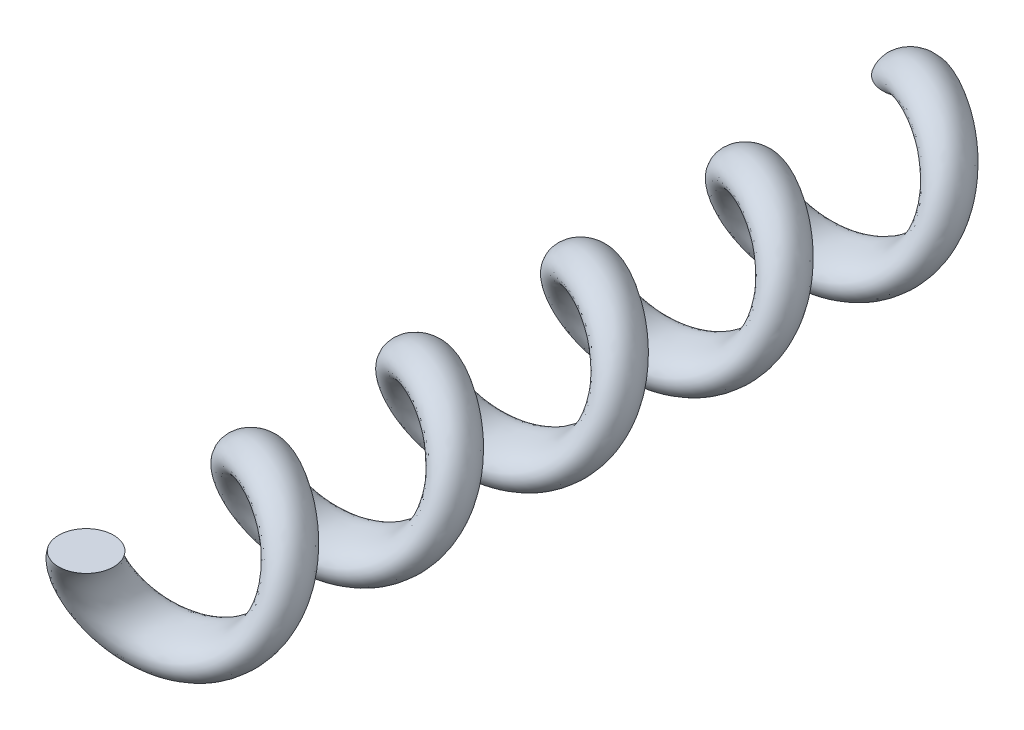
SolidWorks part; units mm, degrees
ref_plane "Front Plane" through (0, 0, 0) normal (0, 0, 1) x (1, 0, 0)
ref_plane "Top Plane" through (0, 0, 0) normal (0, 1, 0) x (1, 0, 0)
ref_plane "Right Plane" through (0, 0, 0) normal (1, 0, 0) x (0, 0, -1)
sketch "Sketch1" plane through (0, 0, 0) normal (0, 0, 1) x (1, 0, 0)
  circle A0 centre (0, 0) radius 2
  dimension "D1" = 4
curve "Helix/Spiral1" pitch 6 height 30 turns 5
ref_plane "Plane1" through (0, 1.4142, 0) normal (0, 1, 0) x (1, 0, 0)
sketch "Sketch2" plane through (0, 1.4142, 0) normal (0, 1, 0) x (1, 0, 0)
  circle A0 centre (-1.4142, 0) radius 1
  spline S0 degree 3 poles (-1.4142, 0) (-1.2301, -0.1243) (-0.7849, -0.3753) (-0.0001, -0.7499) (0.7853, -1.125) (1.451, -1.5) (1.8959, -1.875) (2.0521, -2.25) (1.8959, -2.625) (1.451, -3) (0.5634, -3.5) (-0.5634, -4) (-1.451, -4.5) (-1.8959, -4.875) (-2.0521, -5.25) (-1.8959, -5.625) (-1.451, -6) (-0.5634, -6.5) (0.5634, -7) (1.451, -7.5) (1.8959, -7.875) (2.0521, -8.25) (1.8959, -8.625) (1.451, -9) (0.5634, -9.5) (-0.5634, -10) (-1.451, -10.5) (-1.8959, -10.875) (-2.0521, -11.25) (-1.8959, -11.625) (-1.451, -12) (-0.5634, -12.5) (0.5634, -13) (1.451, -13.5) (1.8959, -13.875) (2.0521, -14.25) (1.8959, -14.625) (1.451, -15) (0.5634, -15.5) (-0.5634, -16) (-1.451, -16.5) (-1.8959, -16.875) (-2.0521, -17.25) (-1.8959, -17.625) (-1.451, -18) (-0.5634, -18.5) (0.5634, -19) (1.451, -19.5) (1.8959, -19.875) (2.0521, -20.25) (1.8959, -20.625) (1.451, -21) (0.5634, -21.5) (-0.5634, -22) (-1.451, -22.5) (-1.8959, -22.875) (-2.0521, -23.25) (-1.8959, -23.625) (-1.451, -24) (-0.5634, -24.5) (0.5634, -25) (1.451, -25.5) (1.8959, -25.875) (2.0521, -26.25) (1.8959, -26.625) (1.451, -27) (0.5634, -27.5) (-0.5634, -28) (-1.451, -28.5) (-1.8959, -28.875) (-2.052, -29.2501) (-1.8963, -29.6247) (-1.5984, -29.8757) (-1.4142, -30) knots 0 0 0 0 0.0125 0.025 0.0375 0.05 0.0625 0.075 0.0875 0.1 0.1125 0.1375 0.15 0.1625 0.175 0.1875 0.2 0.2125 0.2375 0.25 0.2625 0.275 0.2875 0.3 0.3125 0.3375 0.35 0.3625 0.375 0.3875 0.4 0.4125 0.4375 0.45 0.4625 0.475 0.4875 0.5 0.5125 0.5375 0.55 0.5625 0.575 0.5875 0.6 0.6125 0.6375 0.65 0.6625 0.675 0.6875 0.7 0.7125 0.7375 0.75 0.7625 0.775 0.7875 0.8 0.8125 0.8375 0.85 0.8625 0.875 0.8875 0.9 0.9125 0.9375 0.95 0.9625 0.975 0.9875 1 1 1 1 construction
  dimension "D1" = 2
sweep "Sweep1" add profiles "Sketch2" path "Helix/Spiral1"
